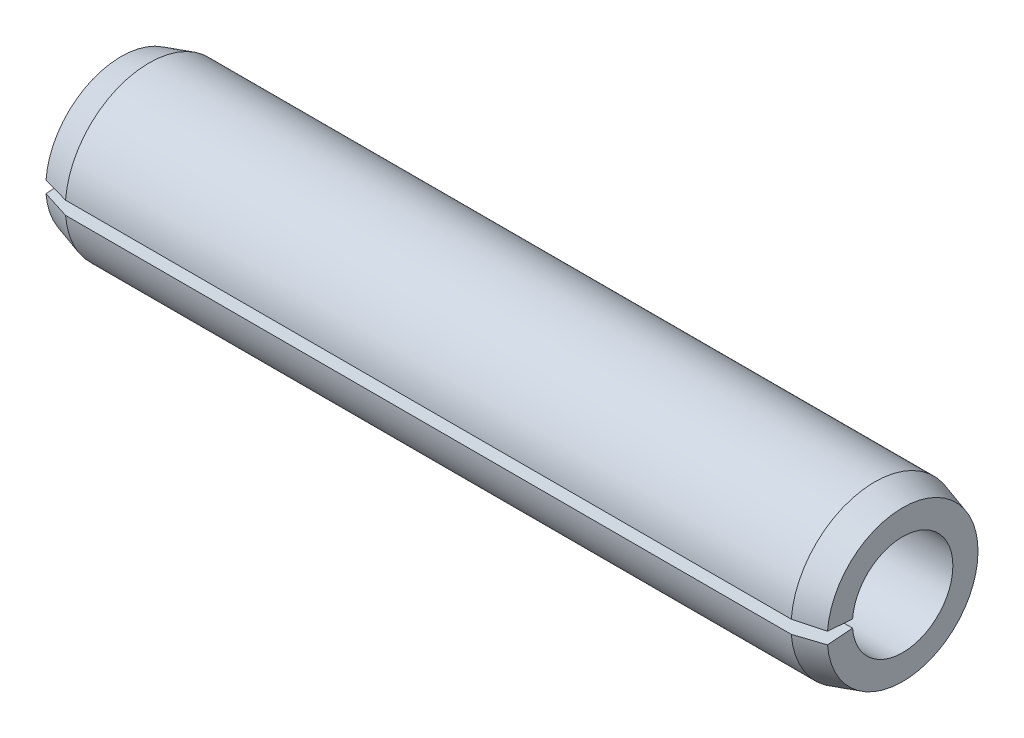
SolidWorks part; units mm, degrees
ref_plane "Plane1" through (0, 0, 0) normal (0, 0, 1) x (1, 0, 0)
ref_plane "Plane2" through (0, 0, 0) normal (0, 1, 0) x (1, 0, 0)
ref_plane "Plane3" through (0, 0, 0) normal (1, 0, 0) x (0, 0, -1)
other "Configuration Table"
sketch "Sketch1" plane through (0, 0, 0) normal (0, 0, 1) x (1, 0, 0)
  line L0 (-9.525, 0) -> (111.125, 0) construction
  line L1 (0, 0.9) -> (14, 0.9)
  line L2 (14, 0.9) -> (14, 1.35)
  line L3 (14, 1.35) -> (13.5, 1.5)
  line L4 (13.5, 1.5) -> (0.5, 1.5)
  line L5 (0.5, 1.5) -> (0, 1.35)
  line L7 (0, 1.35) -> (0, 0.9)
  dimension "Diameter" = 3
  dimension "Thickness" = 0.6
  dimension "Length" = 14
  dimension "Chamfer_len" = 0.5
  dimension "D1" = 2.7
  dimension "D2" = 2.7
  dimension "D3" = 0.5
revolve "Base-Revolve" add sketch "Sketch1" angle 360 about L0
sketch "Sketch2" plane through (0, 0, 0) normal (-1, 0, 0) x (0, -1, 0)
  line L0 (0, 0) -> (0.12, 1.5253)
  line L1 (0, -3.175) -> (0, 12.7) construction
  line L2 (0, 0) -> (-0.12, 1.5253)
  arc A0 (0.12, 1.5253) -> (-0.12, 1.5253) centre (0, 0) ccw
  dimension "Gap_ang" = 9
  dimension "D1" = 1.53
extrude "Gap" cut sketch "Sketch2" against normal through all
equation "\"D1@Sketch2\" = \"Diameter@Sketch1\" * 0.51"
equation "\"D1@Sketch1\" = \"Diameter@Sketch1\" -  ( \"Thickness@Sketch1\" / 2 ) "
equation "\"D2@Sketch1\" = \"D1@Sketch1\""
equation "\"D3@Sketch1\" = \"Chamfer_len@Sketch1\""
